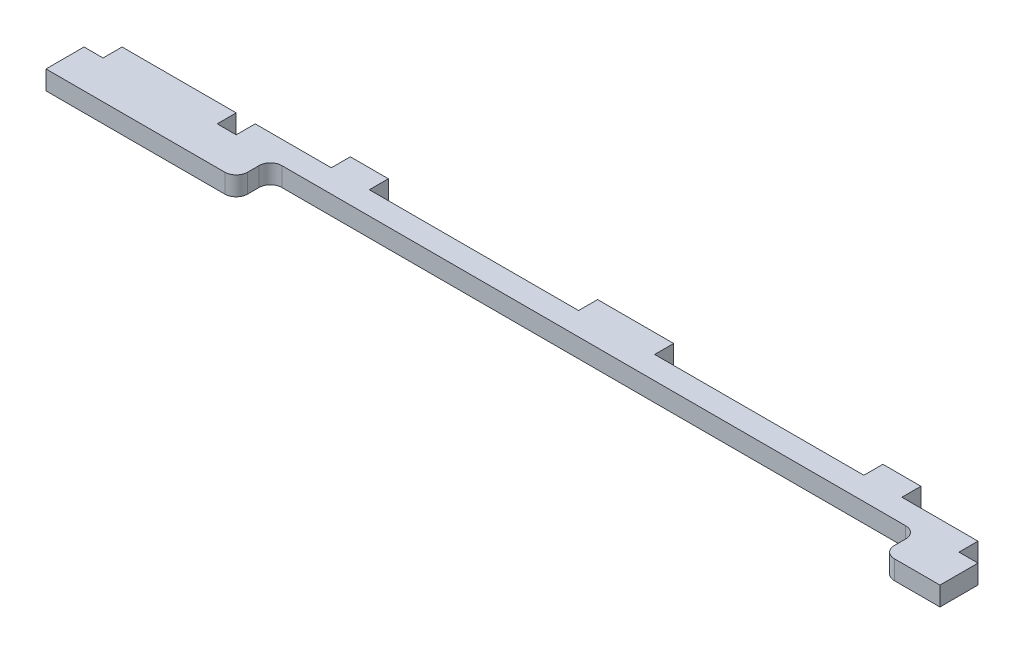
SolidWorks part; units mm, degrees
ref_plane "前视基准面" through (0, 0, 0) normal (0, 0, 1) x (1, 0, 0)
ref_plane "上视基准面" through (0, 0, 0) normal (0, 1, 0) x (1, 0, 0)
ref_plane "右视基准面" through (0, 0, 0) normal (1, 0, 0) x (0, 0, -1)
sketch "草图1" plane through (0, 0, 0) normal (0, 1, 0) x (1, 0, 0)
  line L0 (-5, 23.6086) -> (-5, 10) construction
  line L1 (-5, 0) -> (7, 0)
  line L2 (0, 10) -> (0, 15)
  line L3 (0, 15) -> (20, 15)
  line L4 (190, 10) -> (190, 15)
  line L5 (-7.8366, 20) -> (191.286, 20) construction
  line L6 (195, 26.5505) -> (195, -20.0559) construction
  line L7 (30, 15) -> (85, 15)
  line L8 (105, 15) -> (160, 15)
  line L9 (20, 15) -> (20, 20)
  line L10 (20, 20) -> (30, 20)
  line L11 (30, 15) -> (30, 20)
  line L12 (170, 15) -> (190, 15)
  line L13 (85, 15) -> (85, 20)
  line L14 (85, 20) -> (105, 20)
  line L15 (105, 15) -> (105, 20)
  line L16 (10, 3) -> (10, 6)
  line L17 (160, 15) -> (160, 20)
  line L18 (160, 20) -> (170, 20)
  line L19 (170, 15) -> (170, 20)
  line L20 (0, 10) -> (-5, 10)
  line L21 (13, 9) -> (177, 9)
  line L22 (180, 6) -> (180, 3)
  line L24 (190, 10) -> (195, 10)
  line L25 (183, 0) -> (195, 0)
  line L26 (-5, 0) -> (-40, 0)
  line L27 (195, 10) -> (195, 0)
  line L28 (-40, 0) -> (-40, 10)
  line L29 (-40, 10) -> (-35, 10)
  line L30 (-35, 10) -> (-35, 15)
  line L31 (-35, 15) -> (-5, 15)
  line L32 (-5, 15) -> (-5, 10)
  line L33 (-5, 0) -> (-5, -17.2688) construction
  arc A0 (177, 9) -> (180, 6) centre (177, 6) cw
  arc A1 (10, 6) -> (13, 9) centre (13, 6) cw
  arc A2 (180, 3) -> (183, 0) centre (183, 3) ccw
  arc A3 (10, 3) -> (7, 0) centre (7, 3) cw
  point P43 (180, 0)
  dimension "D16" = 3
  dimension "D2" = 190
  dimension "D3" = 5
  dimension "D4" = 5
  dimension "D5" = 5
  dimension "D6" = 10
  dimension "D7" = 5
  dimension "D8" = 20
  dimension "D9" = 10
  dimension "D10" = 20
  dimension "D11" = 85
  dimension "D12" = 10
  dimension "D13" = 20
  dimension "D14" = 10
  dimension "D15" = 6
  dimension "D17" = 15
extrude "凸台-拉伸2" add sketch "草图1" along normal blind 5
